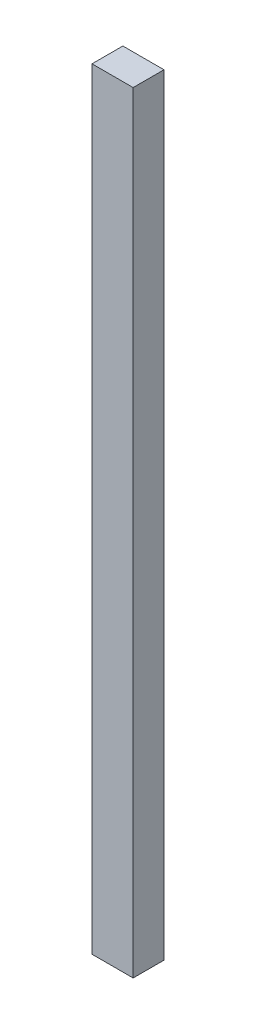
SolidWorks part; units mm, degrees
ref_plane "Plan de face" through (0, 0, 0) normal (0, 0, 1) x (1, 0, 0)
ref_plane "Plan de dessus" through (0, 0, 0) normal (0, 1, 0) x (1, 0, 0)
ref_plane "Plan de droite" through (0, 0, 0) normal (1, 0, 0) x (0, 0, -1)
sketch "Esquisse1" plane through (0, 0, 0) normal (0, 0, 1) x (1, 0, 0)
  line L1 (0, 0) -> (40, 0)
  line L2 (0, 0) -> (0, -750)
  line L3 (0, -750) -> (40, -750)
  line L4 (40, 0) -> (40, -750)
  dimension "D1" = 40
  dimension "D2" = 750
extrude "Boss.-Extru.1" add sketch "Esquisse1" along normal blind 30
